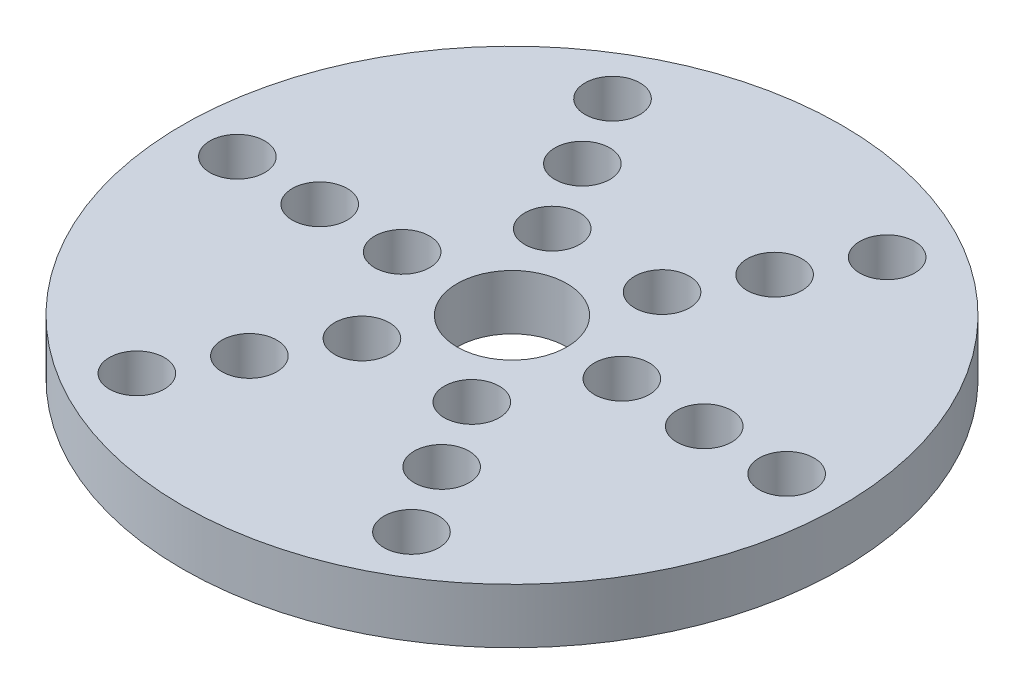
SolidWorks part; units mm, degrees
ref_plane "Front Plane" through (0, 0, 0) normal (0, 0, 1) x (1, 0, 0)
ref_plane "Top Plane" through (0, 0, 0) normal (0, 1, 0) x (1, 0, 0)
ref_plane "Right Plane" through (0, 0, 0) normal (1, 0, 0) x (0, 0, -1)
sketch "Sketch1" plane through (0, 0, 0) normal (0, 1, 0) x (1, 0, 0)
  line L0 (0, 0) -> (-60, 0) construction
  circle A0 centre (0, 0) radius 60
  circle A1 centre (0, 0) radius 10
  circle A2 centre (0, 0) radius 20 construction
  circle A3 centre (0, 0) radius 35 construction
  circle A4 centre (0, 0) radius 50 construction
  circle A5 centre (-20, 0) radius 5
  circle A6 centre (-35, 0) radius 5
  circle A7 centre (-50, 0) radius 5
  circle A8 centre (-10, 17.3205) radius 5
  circle A9 centre (10, 17.3205) radius 5
  circle A10 centre (20, 0) radius 5
  circle A11 centre (10, -17.3205) radius 5
  circle A12 centre (-10, -17.3205) radius 5
  circle A13 centre (-17.5, 30.3109) radius 5
  circle A14 centre (17.5, 30.3109) radius 5
  circle A15 centre (35, 0) radius 5
  circle A16 centre (17.5, -30.3109) radius 5
  circle A17 centre (-17.5, -30.3109) radius 5
  circle A18 centre (-25, 43.3013) radius 5
  circle A19 centre (25, 43.3013) radius 5
  circle A20 centre (50, 0) radius 5
  circle A21 centre (25, -43.3013) radius 5
  circle A22 centre (-25, -43.3013) radius 5
  point P26 (0, 0)
  point P38 (0, 0)
  point P49 (0, 0)
  dimension "D1" = 120
  dimension "D2" = 20
  dimension "D3" = 6
  dimension "D4" = 6
  dimension "D5" = 6
extrude "Boss-Extrude1" add sketch "Sketch1" along normal blind 10
